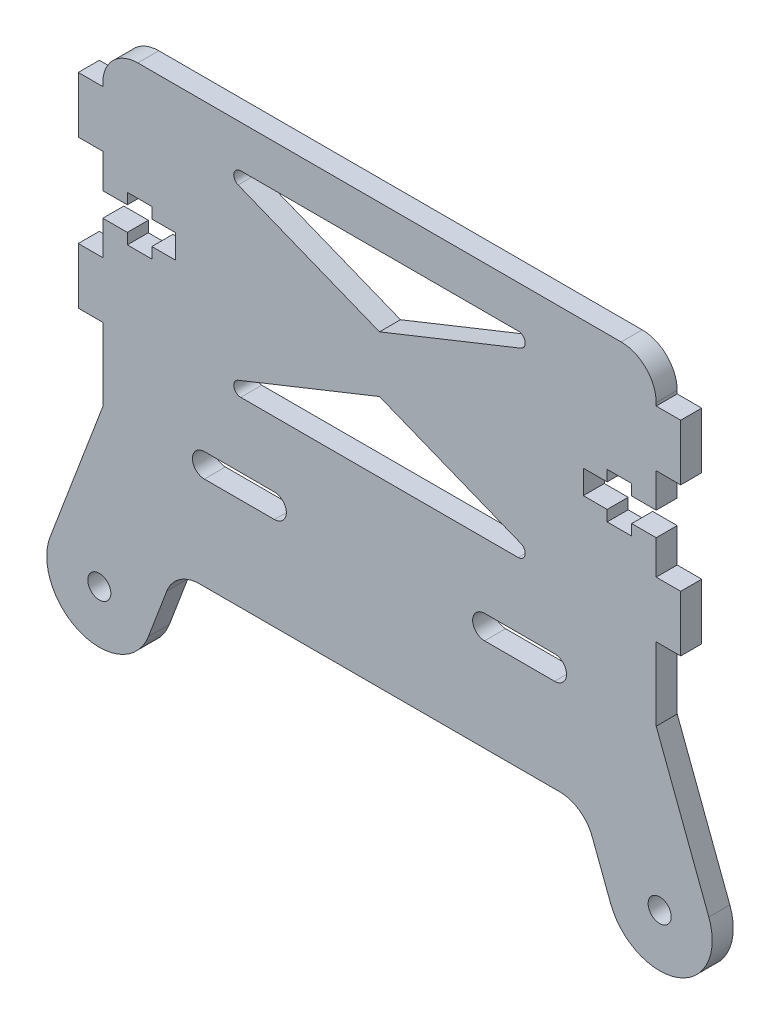
SolidWorks part; units mm, degrees
material "Thornel Mat VMA"
ref_plane "前视基准面" through (0, 0, 0) normal (0, 0, 1) x (1, 0, 0)
ref_plane "上视基准面" through (0, 0, 0) normal (0, 1, 0) x (1, 0, 0)
ref_plane "右视基准面" through (0, 0, 0) normal (1, 0, 0) x (0, 0, -1)
sketch "草图1" plane through (0, 0, 0) normal (0, 0, 1) x (1, 0, 0)
  line L0 (0, 0) -> (5.6798, 15) construction
  line L1 (5.6798, 15) -> (74.3202, 15) construction
  line L2 (74.3202, 15) -> (80, 0) construction
  line L3 (40, 15) -> (40, 0) construction
  line L4 (0, 0) -> (51.3681, 0) construction
  line L5 (7.014, -2.6559) -> (10.8595, 7.5)
  line L6 (10.8595, 7.5) -> (69.1405, 7.5)
  line L7 (69.1405, 7.5) -> (72.986, -2.6559)
  line L8 (-7.014, 2.6559) -> (0.5, 22.5)
  line L10 (79.5, 22.5) -> (87.014, 2.6559)
  line L20 (0.5, 22.5) -> (79.5, 22.5) construction
  line L21 (0.5, 22.5) -> (0.5, 32.925)
  line L22 (0.5, 67.5) -> (79.5, 67.5)
  line L23 (79.5, 67.5) -> (79.5, 62.075)
  line L24 (0.5, 22.5) -> (79.5, 22.5) construction
  line L25 (15, 22.5) -> (25, 22.5) construction
  line L26 (15, 24.2) -> (25, 24.2)
  line L27 (15, 20.8) -> (25, 20.8)
  line L28 (65, 22.5) -> (55, 22.5) construction
  line L29 (65, 24.2) -> (55, 24.2)
  line L30 (65, 20.8) -> (55, 20.8)
  line L31 (0.5, 47.5) -> (79.5, 47.5) construction
  line L32 (40, 67.5) -> (40, 22.5) construction
  line L35 (0.5, 32.925) -> (-3, 32.925)
  line L38 (-3, 32.925) -> (-3, 40.925)
  line L41 (79.5, 32.925) -> (83, 32.925)
  line L44 (-3, 40.925) -> (0.5, 40.925)
  line L45 (0.5, 54.075) -> (-3, 54.075)
  line L46 (-3, 54.075) -> (-3, 62.075)
  line L47 (-3, 62.075) -> (0.5, 62.075)
  line L48 (0.5, 40.925) -> (0.5, 54.075)
  line L49 (0.5, 62.075) -> (0.5, 67.5)
  line L50 (83, 62.075) -> (79.5, 62.075)
  line L51 (83, 54.075) -> (83, 62.075)
  line L52 (79.5, 54.075) -> (83, 54.075)
  line L53 (83, 40.925) -> (79.5, 40.925)
  line L54 (83, 32.925) -> (83, 40.925)
  line L55 (79.5, 32.925) -> (79.5, 22.5)
  line L56 (79.5, 54.075) -> (79.5, 40.925)
  arc A0 (7.014, -2.6559) -> (-7.014, 2.6559) centre (0, 0) cw
  arc A1 (72.986, -2.6559) -> (87.014, 2.6559) centre (80, 0) ccw
  circle A2 centre (0, 0) radius 1.65
  circle A3 centre (80, 0) radius 1.65
  arc A4 (15, 24.2) -> (15, 20.8) centre (15, 22.5) ccw
  arc A5 (25, 20.8) -> (25, 24.2) centre (25, 22.5) ccw
  arc A6 (65, 24.2) -> (65, 20.8) centre (65, 22.5) cw
  arc A7 (55, 20.8) -> (55, 24.2) centre (55, 22.5) cw
  point P20 (20, 22.5)
  point P29 (60, 22.5)
  point P47 (30, 47.5)
  dimension "D9" = 3.3
  dimension "D11" = 8
  dimension "D12" = 8
  dimension "D13" = 13.15
  dimension "D1" = 80
  dimension "D2" = 15
  dimension "D3" = 79
  dimension "D6" = 45
  dimension "D7" = 10
  dimension "D8" = 3.4
  dimension "D10" = 20
  dimension "D20" = 20
  dimension "D14" = 3.5
  dimension "D4" = 7.5
  dimension "D5" = 7.5
extrude "凸台-拉伸1" add sketch "草图1" along normal blind 3
fillet "圆角1" radius 5 4 edges at (69.1405, 7.5, 1.5) (10.8595, 7.5, 1.5) (79.5, 67.5, 1.5) (0.5, 67.5, 1.5)
sketch "草图3" plane through (0, 0, 3) normal (0, 0, 1) x (1, 0, 0)
  line L0 (0.5, 47.5) -> (79.5, 47.5) construction
  line L1 (0.5, 54.075) -> (0.5, 40.925) construction
  line L2 (79.5, 40.925) -> (79.5, 54.075) construction
  line L3 (0.5, 45.8) -> (4, 45.8)
  line L4 (4, 45.8) -> (4, 44.25)
  line L5 (4, 44.25) -> (7.5, 44.25)
  line L6 (7.5, 44.25) -> (7.5, 45.8)
  line L7 (7.5, 45.8) -> (10.9, 45.8)
  line L8 (10.9, 45.8) -> (10.9, 49.2)
  line L9 (0.5, 45.8) -> (0.5, 49.2)
  line L10 (40, 7.5) -> (40, 67.5) construction
  line L11 (14.3127, 7.5) -> (65.6873, 7.5) construction
  line L12 (74.5, 67.5) -> (5.5, 67.5) construction
  line L13 (7.5, 49.2) -> (10.9, 49.2)
  line L14 (7.5, 50.75) -> (7.5, 49.2)
  line L15 (4, 50.75) -> (7.5, 50.75)
  line L16 (4, 49.2) -> (4, 50.75)
  line L17 (0.5, 49.2) -> (4, 49.2)
  line L18 (79.5, 49.2) -> (76, 49.2)
  line L19 (76, 49.2) -> (76, 50.75)
  line L20 (76, 50.75) -> (72.5, 50.75)
  line L21 (72.5, 50.75) -> (72.5, 49.2)
  line L22 (72.5, 49.2) -> (69.1, 49.2)
  line L23 (79.5, 45.8) -> (79.5, 49.2)
  line L24 (69.1, 45.8) -> (69.1, 49.2)
  line L25 (72.5, 45.8) -> (69.1, 45.8)
  line L26 (72.5, 44.25) -> (72.5, 45.8)
  line L27 (76, 44.25) -> (72.5, 44.25)
  line L28 (76, 45.8) -> (76, 44.25)
  line L29 (79.5, 45.8) -> (76, 45.8)
  line L30 (40, 51.5) -> (15, 61.5)
  line L31 (15, 61.5) -> (65, 61.5)
  line L32 (65, 61.5) -> (40, 51.5)
  line L33 (65, 33.5) -> (40, 43.5)
  line L34 (15, 33.5) -> (65, 33.5)
  line L35 (40, 43.5) -> (15, 33.5)
  point P21 (10.9, 47.5)
  point P37 (69.1, 47.5)
  dimension "D1" = 3.4
  dimension "D2" = 3.5
  dimension "D3" = 3.5
  dimension "D4" = 3.4
  dimension "D5" = 6.5
  dimension "D6" = 6
  dimension "D7" = 50
  dimension "D8" = 8
extrude "切除-拉伸1" cut sketch "草图3" against normal through all
fillet "圆角2" radius 1 4 edges at (15, 33.5, 1.5) (15, 61.5, 1.5) (65, 61.5, 1.5) (65, 33.5, 1.5)
